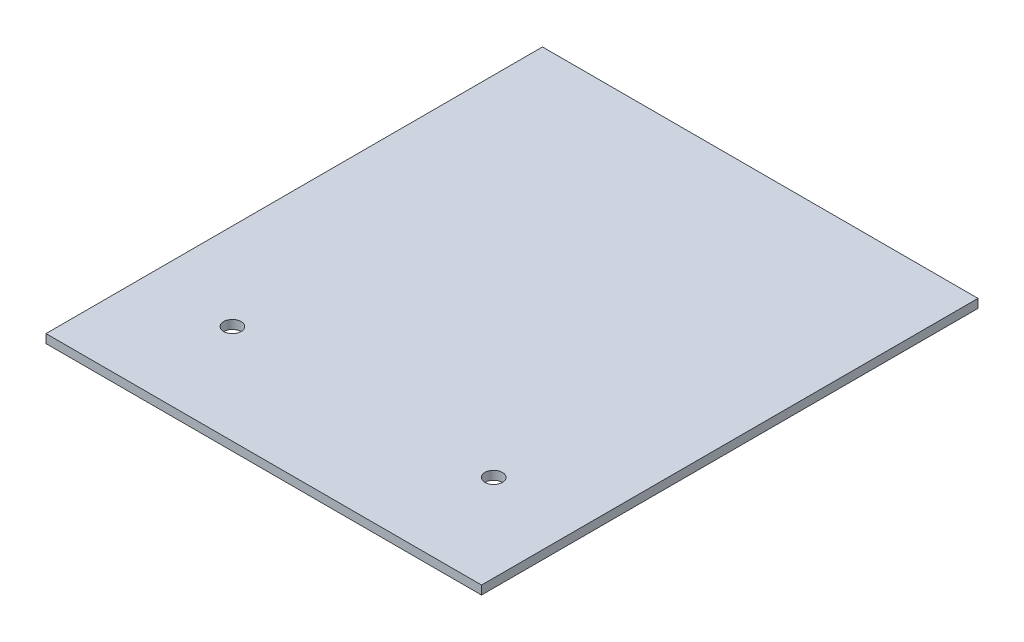
SolidWorks part; units mm, degrees
ref_plane "前视基准面" through (0, 0, 0) normal (0, 0, 1) x (1, 0, 0)
ref_plane "上视基准面" through (0, 0, 0) normal (0, 1, 0) x (1, 0, 0)
ref_plane "右视基准面" through (0, 0, 0) normal (1, 0, 0) x (0, 0, -1)
sketch "草图1" plane through (0, 0, 0) normal (0, 1, 0) x (1, 0, 0)
  line L0 (-75, -85.5) -> (75, -85.5) construction
  line L1 (-125, -142.5) -> (125, -142.5)
  line L2 (-125, -142.5) -> (-125, 142.5)
  line L3 (-125, 142.5) -> (125, 142.5)
  line L4 (125, -142.5) -> (125, 142.5)
  line L5 (-125, -142.5) -> (125, 142.5) construction
  line L6 (-125, 142.5) -> (125, -142.5) construction
  circle A0 centre (-75, -85.5) radius 5
  circle A1 centre (75, -85.5) radius 5
  point P0 (0, 0)
  dimension "D4" = 10
  dimension "D5" = 10
  dimension "D1" = 285
  dimension "D2" = 250
  dimension "D3" = 150
extrude "凸台-拉伸1" add sketch "草图1" along normal blind 5
